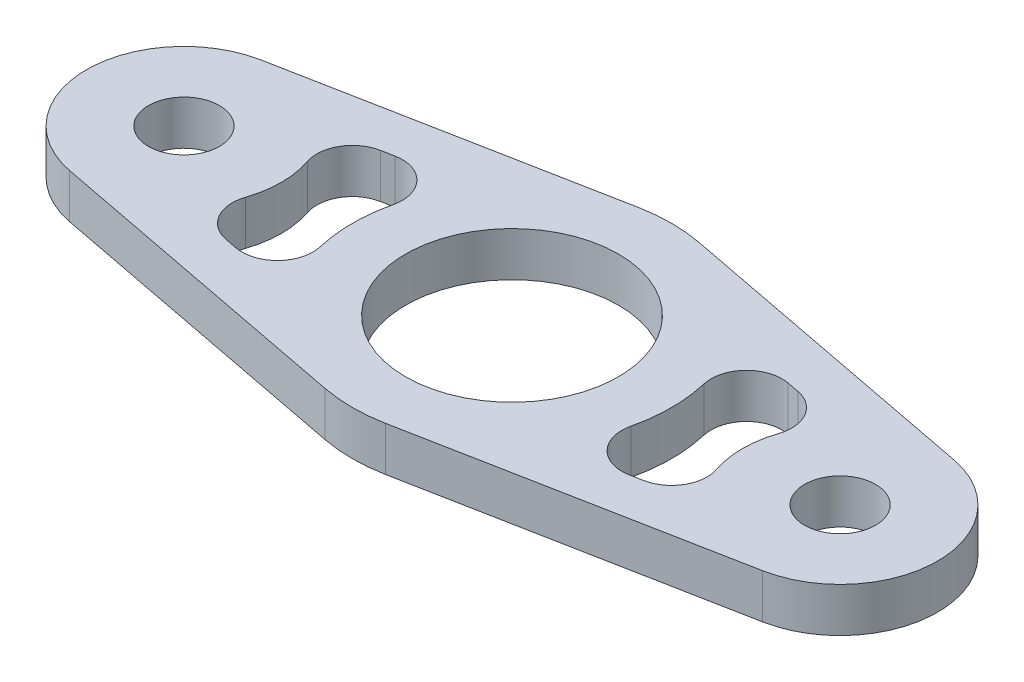
SolidWorks part; units mm, degrees
ref_plane "Front Plane" through (0, 0, 0) normal (0, 0, 1) x (1, 0, 0)
ref_plane "Top Plane" through (0, 0, 0) normal (0, 1, 0) x (1, 0, 0)
ref_plane "Right Plane" through (0, 0, 0) normal (1, 0, 0) x (0, 0, -1)
sketch "Sketch1" plane through (0, 0, 0) normal (0, 1, 0) x (1, 0, 0)
  line L0 (-39.0811, 10.8013) -> (-3.4054, 17.6749)
  line L1 (-29.0821, 7.6359) -> (-14.6845, 10.4098)
  line L2 (-37, 0) -> (0, 0) construction
  line L3 (-29.0821, -7.6359) -> (-14.6845, -10.4098)
  line L4 (-39.0811, -10.8013) -> (-3.4054, -17.6749)
  line L5 (-38.1351, 5.8916) -> (-2.4595, 12.7652) construction
  line L6 (0, 0) -> (0, 32.835) construction
  line L7 (39.0811, -10.8013) -> (3.4054, -17.6749)
  line L8 (29.0821, -7.6359) -> (14.6845, -10.4098)
  line L9 (29.0821, 7.6359) -> (14.6845, 10.4098)
  line L10 (39.0811, 10.8013) -> (3.4054, 17.6749)
  circle A0 centre (0, 0) radius 12
  arc A1 (-14.6845, 10.4098) -> (-14.6845, -10.4098) centre (0, 0) ccw
  circle A2 centre (-37, 0) radius 4
  arc A3 (-39.0811, 10.8013) -> (-39.0811, -10.8013) centre (-37, 0) ccw
  arc A4 (-29.0821, -7.6359) -> (-29.0821, 7.6359) centre (-37, 0) ccw
  arc A5 (-3.4054, -17.6749) -> (3.4054, -17.6749) centre (0, 0) ccw
  circle A6 centre (37, 0) radius 4
  arc A7 (39.0811, 10.8013) -> (39.0811, -10.8013) centre (37, 0) cw
  arc A8 (14.6845, 10.4098) -> (14.6845, -10.4098) centre (0, 0) cw
  arc A9 (29.0821, -7.6359) -> (29.0821, 7.6359) centre (37, 0) cw
  arc A10 (3.4054, 17.6749) -> (-3.4054, 17.6749) centre (0, 0) ccw
  arc A11 (14.6845, -10.4098) -> (14.6845, 10.4098) centre (0, 0) ccw
  dimension "D1" = 24
  dimension "D2" = 36
  dimension "D3" = 8
  dimension "D4" = 22
  dimension "D5" = 37
  dimension "D6" = 5
extrude "Boss-Extrude1" add sketch "Sketch1" along normal mid plane 5 contours L10 A10 L0 A3 L4 A5 L7 A7 A6 A2 A0 L3 A4 L1 A1 A9 L8 A8 L9
fillet "Fillet1" radius 4 8 edges at (29.0821, 0, 7.6359) (14.6845, 0, 10.4098) (29.0821, 0, -7.6359) (14.6845, 0, -10.4098) (-14.6845, 0, 10.4098) (-29.0821, 0, 7.6359) (-29.0821, 0, -7.6359) (-14.6845, 0, -10.4098)
